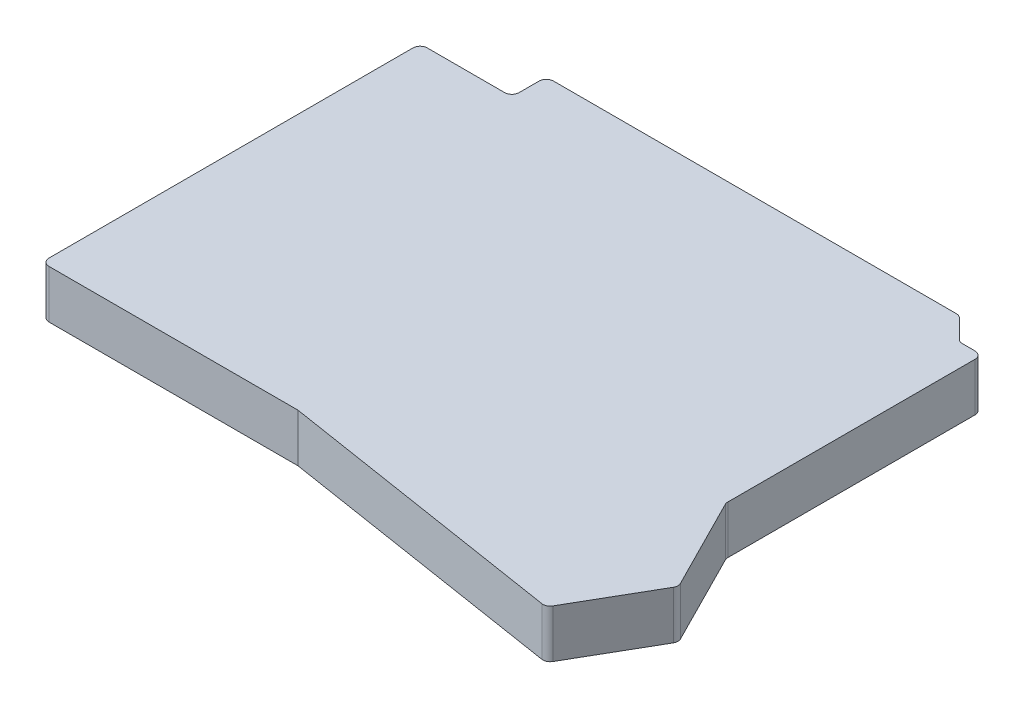
SolidWorks part; units mm, degrees
ref_plane "Front" through (0, 0, 0) normal (0, 0, 1) x (1, 0, 0)
ref_plane "Top" through (0, 0, 0) normal (0, 1, 0) x (1, 0, 0)
ref_plane "Right" through (0, 0, 0) normal (1, 0, 0) x (0, 0, -1)
sketch "Skizze2" plane through (0, 0, 0) normal (0, 1, 0) x (1, 0, 0)
  line L0 (0, 0) -> (0, 55.62)
  line L1 (1.5, 57.12) -> (17.54, 57.12)
  line L2 (19.04, 58.62) -> (19.04, 62.76)
  line L3 (20.54, 64.26) -> (104.0987, 64.26)
  line L4 (114.7551, -30.1079) -> (123.9088, -14.2531)
  line L5 (105.1593, 63.8207) -> (109.0407, 59.9393)
  line L6 (110.1013, 59.5) -> (112.74, 59.5)
  line L7 (114.24, 58) -> (114.24, 6.7081)
  line L8 (0, 0) -> (0, -19.87)
  line L9 (1.5, -21.37) -> (53.0325, -21.37)
  line L10 (53.2661, -21.3883) -> (113.2224, -30.8396)
  line L11 (114.24, -31) -> (162.7359, -31) construction
  line L12 (123.948, -12.8256) -> (114.4017, 6.0305)
  arc A0 (19.04, 62.76) -> (20.54, 64.26) centre (20.54, 62.76) cw
  arc A1 (104.0987, 64.26) -> (105.1593, 63.8207) centre (104.0987, 62.76) cw
  arc A2 (109.0407, 59.9393) -> (110.1013, 59.5) centre (110.1013, 61) ccw
  arc A3 (112.74, 59.5) -> (114.24, 58) centre (112.74, 58) cw
  arc A4 (114.4017, 6.0305) -> (114.24, 6.7081) centre (115.74, 6.7081) cw
  arc A5 (123.9088, -14.2531) -> (123.948, -12.8256) centre (122.6098, -13.5031) ccw
  arc A6 (53.0325, -21.37) -> (53.2661, -21.3883) centre (53.0325, -22.87) cw
  arc A7 (114.7551, -30.1079) -> (113.2224, -30.8396) centre (113.456, -29.3579) cw
  arc A8 (17.54, 57.12) -> (19.04, 58.62) centre (17.54, 58.62) ccw
  arc A9 (0, 55.62) -> (1.5, 57.12) centre (1.5, 55.62) cw
  arc A10 (0, -19.87) -> (1.5, -21.37) centre (1.5, -19.87) ccw
  point P3 (114.24, -31)
  point P14 (0, 0)
  point P18 (19.04, 64.26)
  point P21 (104.72, 64.26)
  point P26 (114.24, 59.5)
  point P29 (114.24, 6.35)
  point P32 (124.3148, -13.55)
  point P35 (53.15, -21.37)
  point P41 (19.04, 57.12)
  point P44 (0, 57.12)
  point P47 (0, -21.37)
  dimension "D14" = 1.5
  dimension "D1" = 57.12
  dimension "D2" = 19.04
  dimension "D3" = 7.14
  dimension "D4" = 85.68
  dimension "D5" = 4.76
  dimension "D6" = 95.2
  dimension "D7" = 90.5
  dimension "D8" = 21.37
  dimension "D9" = 53.15
  dimension "D10" = 45
  dimension "D11" = 60
  dimension "D12" = 17.45
  dimension "D13" = 53.15
extrude "Aufsatz-Linear austragen1" add sketch "Skizze2" along normal blind 10
